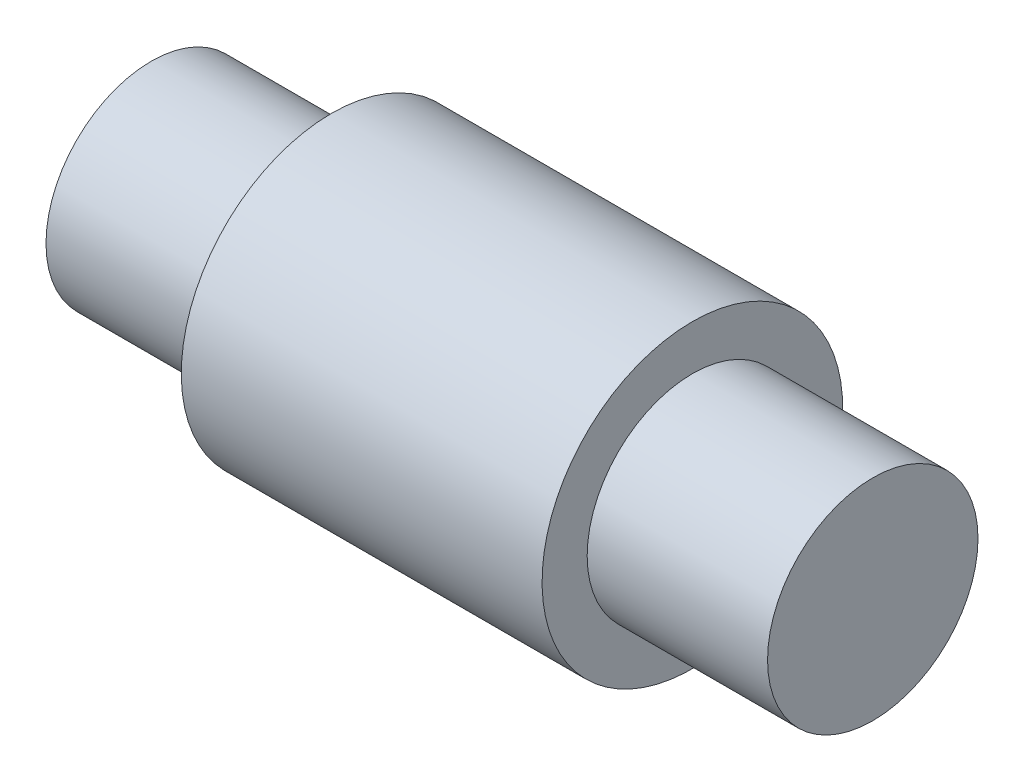
SolidWorks part; units mm, degrees
ref_plane "Front Plane" through (0, 0, 0) normal (0, 0, 1) x (1, 0, 0)
ref_plane "Top Plane" through (0, 0, 0) normal (0, 1, 0) x (1, 0, 0)
ref_plane "Right Plane" through (0, 0, 0) normal (1, 0, 0) x (0, 0, -1)
sketch "Sketch1" plane through (0, 0, 0) normal (0, 0, 1) x (1, 0, 0)
  line L0 (0, 0) -> (0, 3.5)
  line L1 (0, 3.5) -> (6, 3.5)
  line L2 (6, 3.5) -> (6, 5)
  line L3 (6, 5) -> (18, 5)
  line L4 (18, 5) -> (18, 3.5)
  line L5 (18, 3.5) -> (24, 3.5)
  line L6 (24, 3.5) -> (24, 0)
  line L7 (24, 0) -> (0, 0)
  dimension "D1" = 6
  dimension "D2" = 6
  dimension "D3" = 12
  dimension "D4" = 5
  dimension "D5" = 3.5
  dimension "D6" = 3.5
revolve "Revolve1" add sketch "Sketch1" angle 360 about L7
